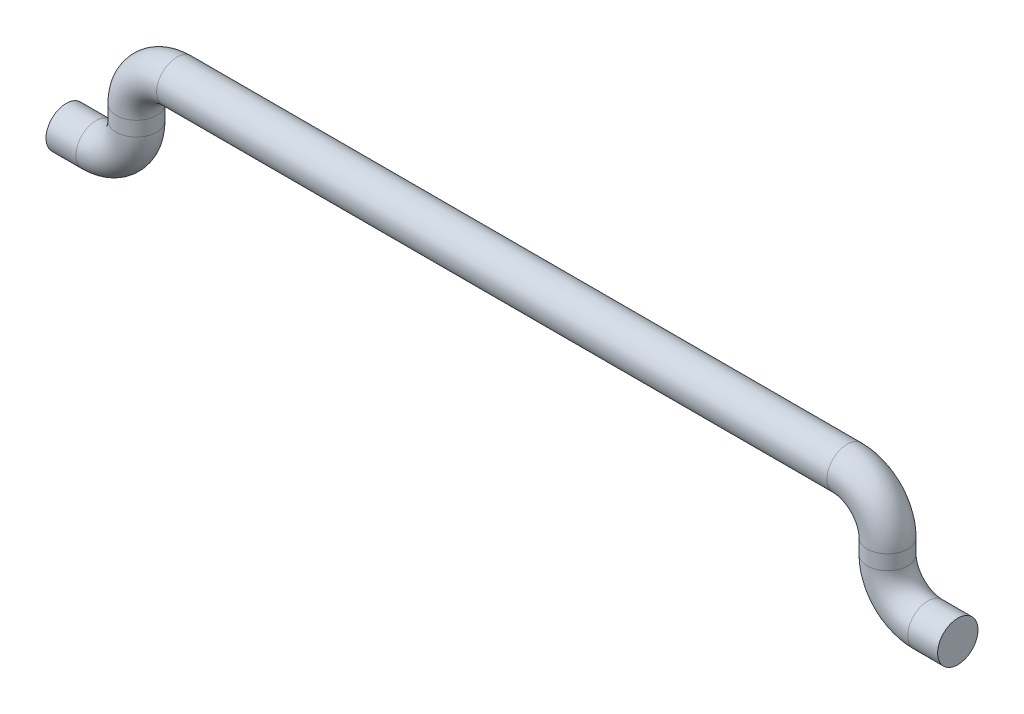
SolidWorks part; units mm, degrees
ref_plane "Alzado" through (0, 0, 0) normal (0, 0, 1) x (1, 0, 0)
ref_plane "Planta" through (0, 0, 0) normal (0, 1, 0) x (1, 0, 0)
ref_plane "Vista lateral" through (0, 0, 0) normal (1, 0, 0) x (0, 0, -1)
sketch "Croquis1" plane through (0, 0, 0) normal (0, 0, 1) x (1, 0, 0)
  line L1 (-25.75, -5.9) -> (-27.6, -5.9)
  line L2 (20.75, 0) -> (-20.75, 0)
  line L3 (23.25, -2.5) -> (23.25, -3.4)
  line L4 (25.75, -5.9) -> (27.6, -5.9)
  line L5 (-23.25, -2.5) -> (-23.25, -3.4)
  arc A0 (23.25, -3.4) -> (25.75, -5.9) centre (25.75, -3.4) ccw
  arc A1 (20.75, 0) -> (23.25, -2.5) centre (20.75, -2.5) cw
  arc A2 (-20.75, 0) -> (-23.25, -2.5) centre (-20.75, -2.5) ccw
  arc A3 (-25.75, -5.9) -> (-23.25, -3.4) centre (-25.75, -3.4) ccw
  point P1 (0, 0)
  point P7 (0, 0)
  point P13 (23.25, -5.9)
  point P16 (23.25, 0)
  point P19 (-23.25, 0)
  point P22 (-23.25, -5.9)
  dimension "D4" = 2.5
  dimension "D1" = 5.9
  dimension "D2" = 46.5
  dimension "D3" = 4.35
  dimension "D5" = 4.35
ref_plane "Plano1" through (27.6, 0, 0) normal (1, 0, 0) x (0, 0, -1)
sketch "Croquis2" plane through (27.6, 0, 0) normal (1, 0, 0) x (0, 0, -1)
  circle A0 centre (0, -5.9) radius 1.25
  dimension "D1" = 2.5
sweep "Barrer1" add profiles "Croquis2" path "Croquis1"
